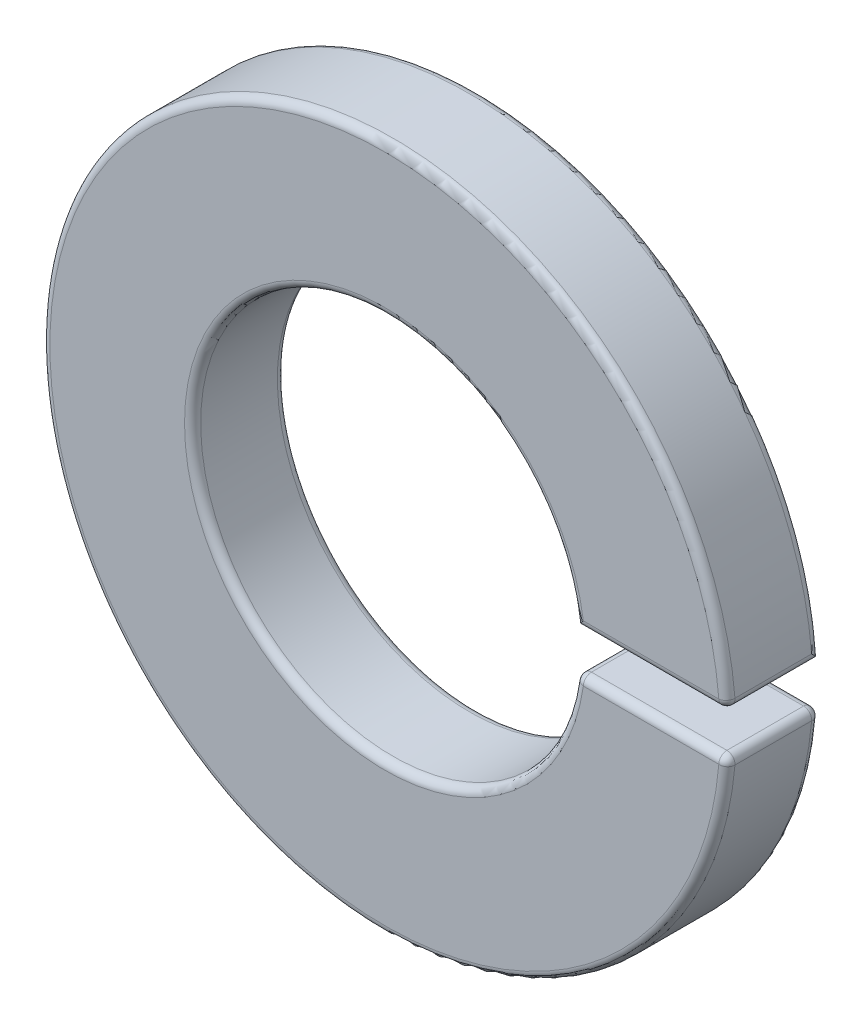
SolidWorks part; units mm, degrees
ref_plane "Plano frontal" through (0, 0, 0) normal (0, 0, 1) x (1, 0, 0)
ref_plane "Plano superior" through (0, 0, 0) normal (0, 1, 0) x (1, 0, 0)
ref_plane "Plano direito" through (0, 0, 0) normal (1, 0, 0) x (0, 0, -1)
sketch "Esboço1" plane through (0, 0, 0) normal (0, 0, 1) x (1, 0, 0)
  line L1 (4.7387, 0.5) -> (8.4853, 0.5)
  line L3 (4.7387, -0.5) -> (8.4853, -0.5)
  arc A0 (8.4853, 0.5) -> (8.4853, -0.5) centre (0, 0) ccw
  arc A1 (4.7387, 0.5) -> (4.7387, -0.5) centre (0, 0) ccw
  dimension "D1" = 17
  dimension "D2" = 9.53
  dimension "D3" = 0.5
  dimension "D4" = 0.5
extrude "Ressalto-extrusão1" add sketch "Esboço1" along normal blind 2.3
fillet "Filete1" radius 0.2 10 edges at (-4.765, 0, 0) (-8.5, 0, 0) (6.612, -0.5, 0) (-4.765, 0, 2.3) (6.612, 0.5, 2.3) (-8.5, 0, 2.3) (6.612, -0.5, 2.3) (4.7387, -0.5, 1.15) (8.4853, -0.5, 1.15) (8.4853, 0.5, 1.15)
